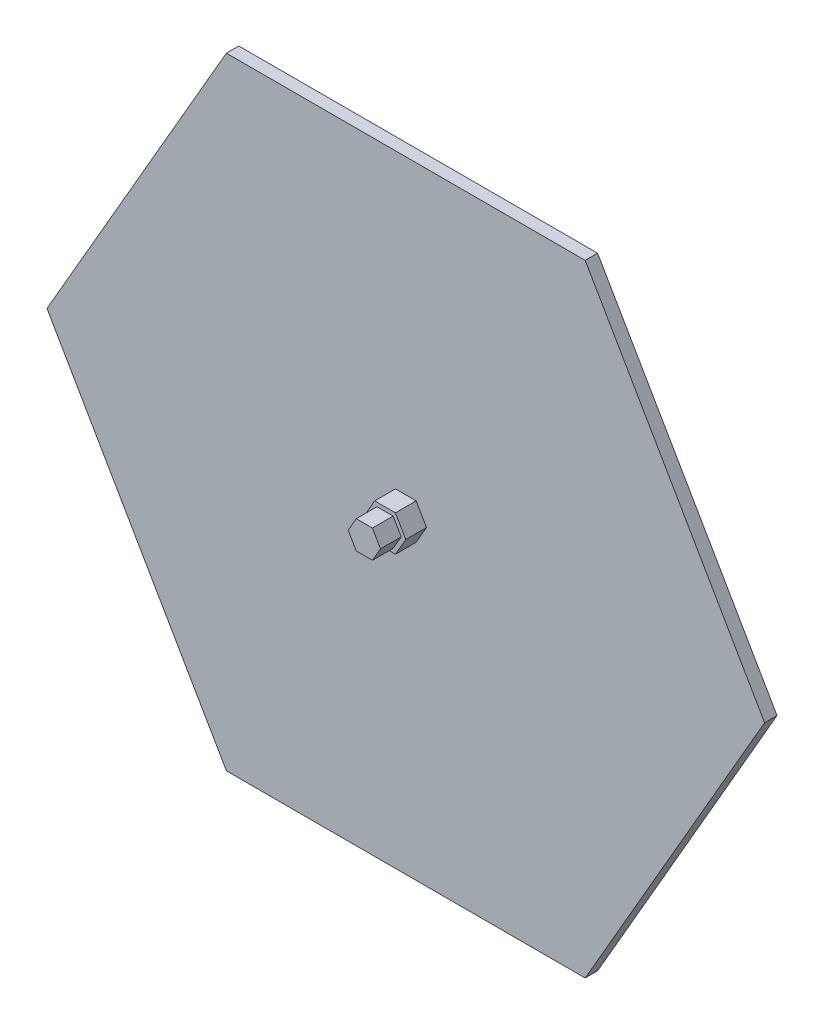
SolidWorks part; units mm, degrees
ref_plane "Alzado" through (0, 0, 0) normal (0, 0, 1) x (1, 0, 0)
ref_plane "Planta" through (0, 0, 0) normal (0, 1, 0) x (1, 0, 0)
ref_plane "Vista lateral" through (0, 0, 0) normal (1, 0, 0) x (0, 0, -1)
ref_plane "Plano1" through (0, 0, 0) normal (0, 0, -1) x (-1, 0, 0)
sketch "Croquis1" plane through (0, 0, 0) normal (0, 0, -1) x (-1, 0, 0)
  line L0 (86.6025, 0) -> (43.3013, 75)
  line L1 (43.3013, 75) -> (-43.3013, 75)
  line L2 (-43.3013, 75) -> (-86.6025, 0)
  line L3 (-86.6025, 0) -> (-43.3013, -75)
  line L4 (-43.3013, -75) -> (43.3013, -75)
  line L5 (43.3013, -75) -> (86.6025, 0)
  line L6 (-86.6025, 0) -> (86.6025, 0) construction
  point P6 (0, 0)
  point P8 (0, 0)
  dimension "D1" = 150
  dimension "D2" = 120
  dimension "D3" = 120
  dimension "D4" = 120
  dimension "D5" = 120
  dimension "D6" = 75
  dimension "D7" = 173.2051
extrude "Saliente-Extruir1" add sketch "Croquis1" against normal blind 3
sketch "Croquis2" plane through (0, 0, 3) normal (0, 0, 1) x (1, 0, 0)
  line L0 (-2.5, 4.3301) -> (2.5, 4.3301)
  line L1 (2.5, 4.3301) -> (5, 0)
  line L2 (5, 0) -> (2.5, -4.3301)
  line L3 (2.5, -4.3301) -> (-2.5, -4.3301)
  line L4 (-2.5, -4.3301) -> (-5, 0)
  line L5 (-5, 0) -> (-2.5, 4.3301)
  line L6 (-5, 0) -> (5, 0) construction
  point P6 (0, 0)
  dimension "D1" = 8.6603
  dimension "D2" = 8.6603
  dimension "D3" = 8.6603
  dimension "D4" = 120
  dimension "D5" = 120
  dimension "D6" = 4.3301
extrude "Saliente-Extruir2" add sketch "Croquis2" along normal blind 5
sketch "Croquis3" plane through (0, 0, 8) normal (0, 0, 1) x (1, 0, 0)
  line L0 (-1.95, -3.3775) -> (-3.9, 0)
  line L1 (-3.9, 0) -> (-1.95, 3.3775)
  line L2 (-1.95, 3.3775) -> (1.95, 3.3775)
  line L3 (1.95, 3.3775) -> (3.9, 0)
  line L4 (3.9, 0) -> (1.95, -3.3775)
  line L5 (1.95, -3.3775) -> (-1.95, -3.3775)
  line L6 (-3.9, 0) -> (3.9, 0) construction
  point P6 (0, 0)
  dimension "D1" = 240
  dimension "D2" = 240
  dimension "D3" = 6.755
  dimension "D4" = 6.755
  dimension "D5" = 6.755
  dimension "D6" = 3.3775
extrude "Saliente-Extruir3" add sketch "Croquis3" along normal blind 5
